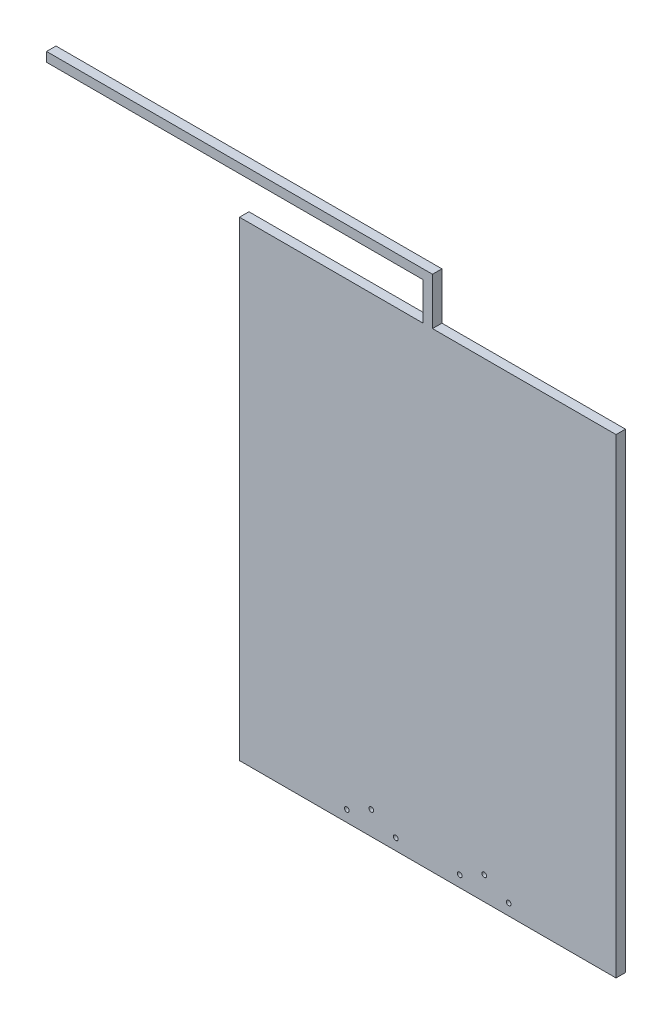
SolidWorks part; units mm, degrees
ref_plane "Front Plane" through (0, 0, 0) normal (0, 0, 1) x (1, 0, 0)
ref_plane "Top Plane" through (0, 0, 0) normal (0, 1, 0) x (1, 0, 0)
ref_plane "Right Plane" through (0, 0, 0) normal (1, 0, 0) x (0, 0, -1)
sketch "Sketch1" plane through (0, 0, 0) normal (0, 0, 1) x (1, 0, 0)
  line L1 (200, -250) -> (-200, -250)
  line L2 (200, -250) -> (200, 250)
  line L3 (200, 250) -> (-200, 250)
  line L4 (-200, -250) -> (-200, 250)
  line L5 (200, -250) -> (-200, 250) construction
  line L6 (200, 250) -> (-200, -250) construction
  point P0 (0, 0)
  dimension "D1" = 400
  dimension "D2" = 500
extrude "Boss-Extrude1" add sketch "Sketch1" along normal blind 10
sketch "Sketch2" plane through (0, 0, 10) normal (0, 0, 1) x (1, 0, 0)
  line L0 (-200, 250) -> (-200, -250) construction
  line L1 (-200, -250) -> (200, -250) construction
  line L2 (200, -250) -> (200, 250) construction
  circle A0 centre (-86, -238) radius 2.5
  circle A1 centre (-60, -225) radius 2.5
  circle A2 centre (-34, -238) radius 2.5
  circle A3 centre (34, -238) radius 2.5
  circle A4 centre (60, -225) radius 2.5
  circle A5 centre (86, -238) radius 2.5
  dimension "D2" = 114
  dimension "D3" = 12
  dimension "D4" = 140
  dimension "D5" = 25
  dimension "D6" = 166
  dimension "D7" = 12
  dimension "D8" = 114
  dimension "D9" = 12
  dimension "D10" = 140
  dimension "D11" = 25
  dimension "D12" = 166
  dimension "D13" = 12
extrude "Cut-Extrude1" cut sketch "Sketch2" against normal through all
sketch "Sketch3" plane through (0, 250, 0) normal (0, 1, 0) x (1, 0, 0)
  line L0 (200, 0) -> (-200, 0) construction
  line L1 (-5, 0) -> (5, 0)
  line L2 (-5, 0) -> (-5, -10)
  line L3 (-5, -10) -> (5, -10)
  line L4 (5, 0) -> (5, -10)
  line L5 (-5, 0) -> (5, -10) construction
  line L6 (-5, -10) -> (5, 0) construction
  line L7 (-200, -10) -> (-200, 0) construction
  point P0 (0, -5)
  point P5 (-14.3836, -16.5116)
  point P10 (-200, -5)
  dimension "D1" = 10
  dimension "D2" = 10
  dimension "D3" = 0
  dimension "D4" = 200
extrude "Boss-Extrude2" add sketch "Sketch3" along normal blind 50
sketch "Sketch4" plane through (-5, 0, 0) normal (-1, 0, 0) x (0, 0, 1)
  line L0 (10, 300) -> (10, 250) construction
  line L1 (0, 300) -> (10, 300)
  line L2 (0, 300) -> (0, 290)
  line L3 (0, 290) -> (10, 290)
  line L4 (10, 300) -> (10, 290)
  line L5 (0, 300) -> (10, 290) construction
  line L6 (0, 290) -> (10, 300) construction
  line L7 (0, 300) -> (10, 300) construction
  point P0 (5, 295)
  dimension "D1" = 10
  dimension "D2" = 10
  dimension "D3" = 0
  dimension "D4" = 0
extrude "Boss-Extrude3" add sketch "Sketch4" along normal blind 400
sketch "Sketch5" plane through (-405, 0, 0) normal (-1, 0, 0) x (0, 0, 1)
  line L0 (10, 290) -> (10, 300) construction
  line L1 (10, 300) -> (0, 300) construction
  circle A0 centre (5, 295) radius 2.5
  point P4 (0, 0)
  point P7 (5, 300)
  dimension "D1" = 5
  dimension "D2" = 5
extrude "Cut-Extrude2" cut sketch "Sketch5" against normal blind 10
